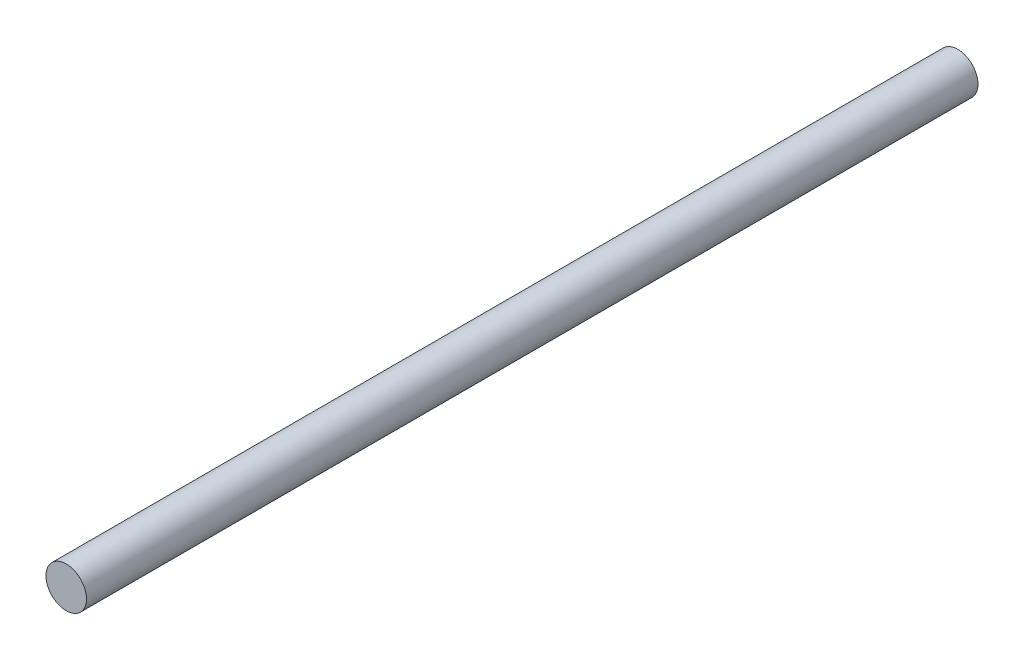
SolidWorks part; units mm, degrees
material "LW-PLA"
ref_plane "Front Plane" through (0, 0, 0) normal (0, 0, 1) x (1, 0, 0)
ref_plane "Top Plane" through (0, 0, 0) normal (0, 1, 0) x (1, 0, 0)
ref_plane "Right Plane" through (0, 0, 0) normal (1, 0, 0) x (0, 0, -1)
sketch "Sketch1" plane through (0, 0, 0) normal (0, 0, 1) x (1, 0, 0)
  circle A0 centre (0, 0) radius 0.75
  dimension "D1" = 1.5
extrude "Boss-Extrude1" add sketch "Sketch1" along normal blind 33
